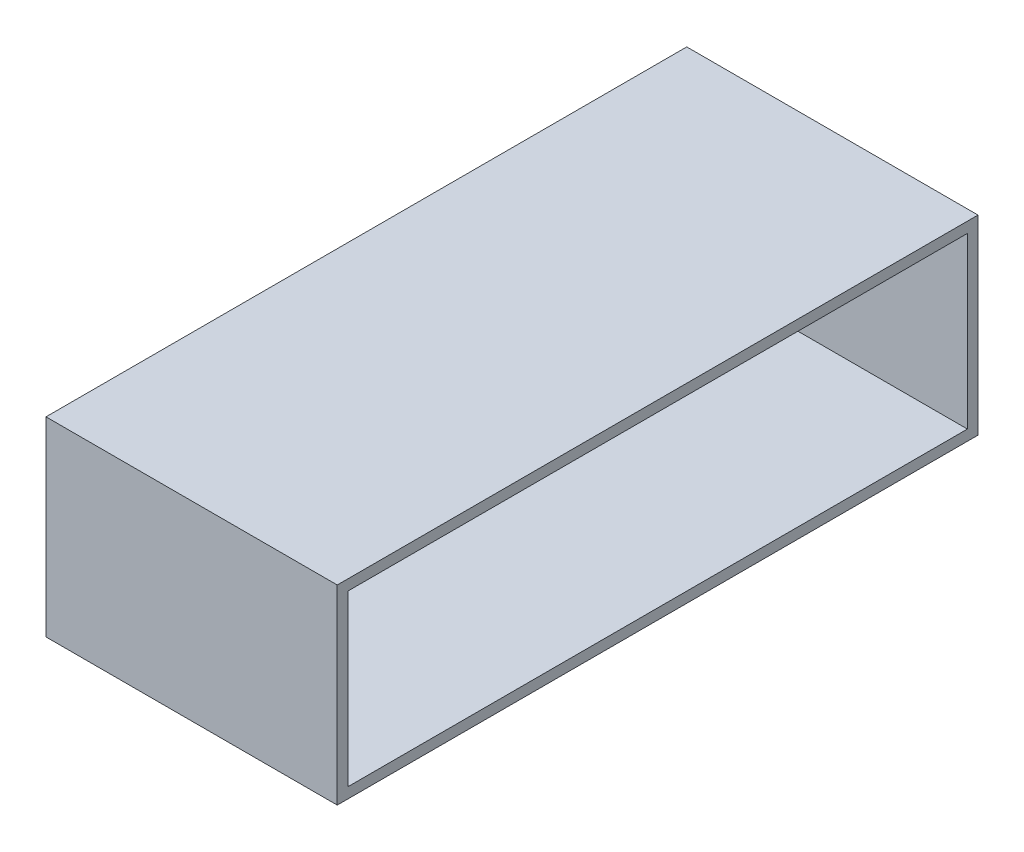
SolidWorks part; units mm, degrees
ref_plane "Front Plane" through (0, 0, 0) normal (0, 0, 1) x (1, 0, 0)
ref_plane "Top Plane" through (0, 0, 0) normal (0, 1, 0) x (1, 0, 0)
ref_plane "Right Plane" through (0, 0, 0) normal (1, 0, 0) x (0, 0, -1)
sketch "Sketch1" plane through (0, 0, 0) normal (1, 0, 0) x (0, 0, -1)
  line L1 (-121, -36) -> (121, -36)
  line L2 (-121, -36) -> (-121, 36)
  line L3 (-121, 36) -> (121, 36)
  line L4 (121, -36) -> (121, 36)
  line L5 (-121, -36) -> (121, 36) construction
  line L6 (-121, 36) -> (121, -36) construction
  point P0 (0, 0)
  dimension "D1" = 242
  dimension "D2" = 72
extrude "Boss-Extrude1" add sketch "Sketch1" against normal blind 110
shell "Shell1" thickness 4
